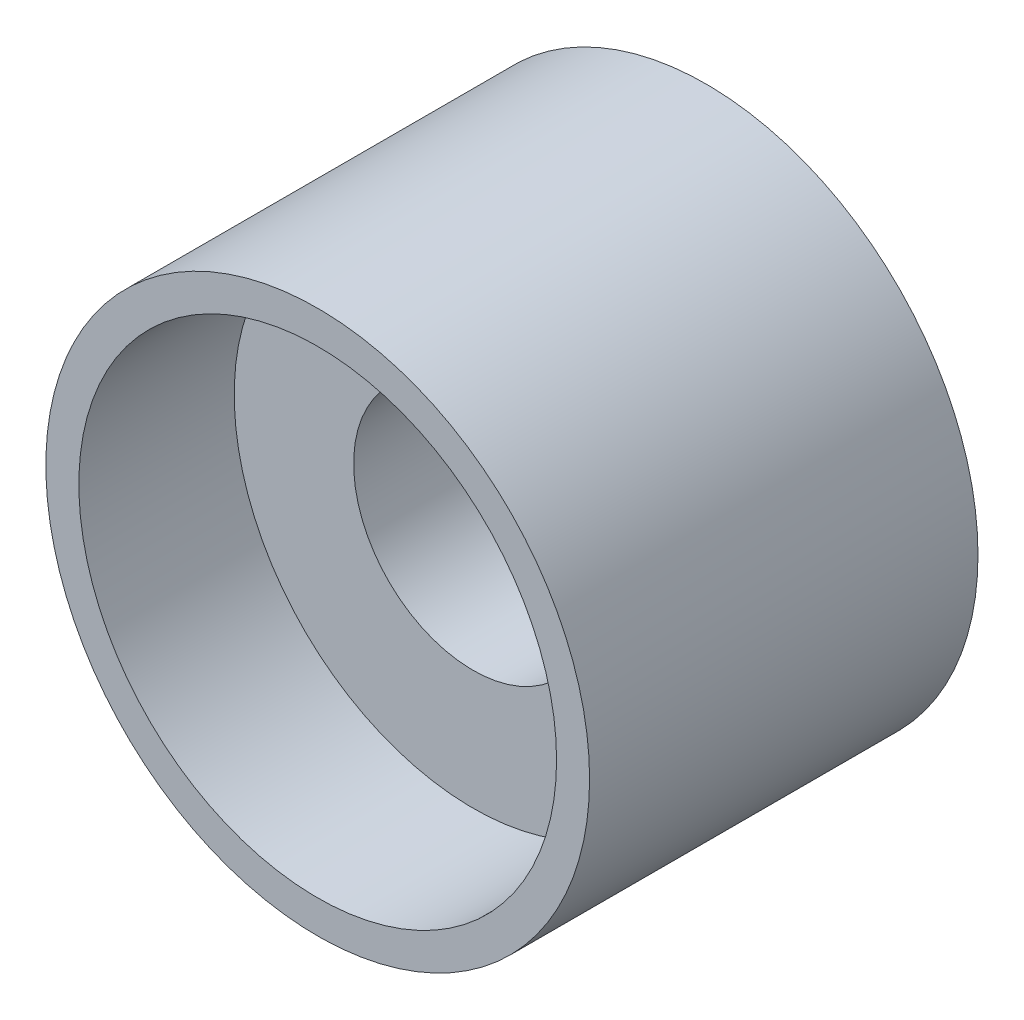
SolidWorks part; units mm, degrees
ref_plane "Front Plane" through (0, 0, 0) normal (0, 0, 1) x (1, 0, 0)
ref_plane "Top Plane" through (0, 0, 0) normal (0, 1, 0) x (1, 0, 0)
ref_plane "Right Plane" through (0, 0, 0) normal (1, 0, 0) x (0, 0, -1)
sketch "Sketch1" plane through (0, 0, 0) normal (0, 0, 1) x (1, 0, 0)
  circle A0 centre (0, 0) radius 14
  circle A1 centre (0, 0) radius 6.15
  dimension "D1" = 28
  dimension "D2" = 12.3
extrude "Boss-Extrude1" add sketch "Sketch1" along normal blind 20
sketch "Sketch2" plane through (0, 0, 20) normal (0, 0, 1) x (1, 0, 0)
  circle A0 centre (0, 0) radius 12.3
  circle A1 centre (0, 0) radius 14 construction
  dimension "D1" = 1.7
extrude "Cut-Extrude1" cut sketch "Sketch2" against normal blind 8
